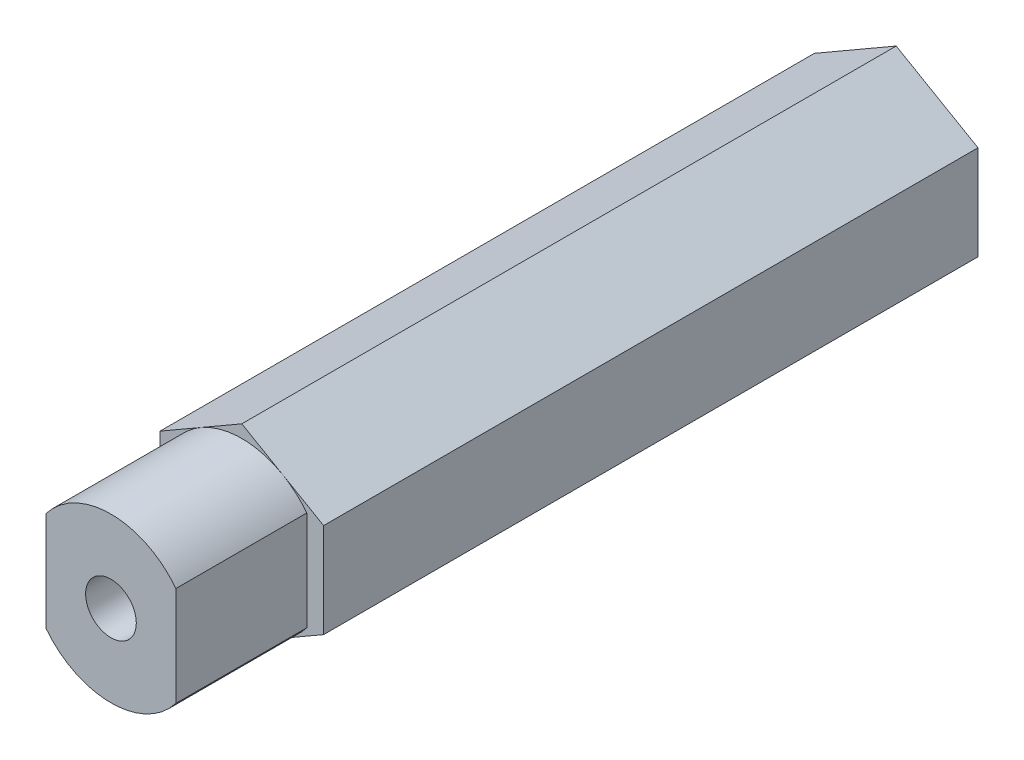
SolidWorks part; units mm, degrees
ref_plane "Front Plane" through (0, 0, 0) normal (0, 0, 1) x (1, 0, 0)
ref_plane "Top Plane" through (0, 0, 0) normal (0, 1, 0) x (1, 0, 0)
ref_plane "Right Plane" through (0, 0, 0) normal (1, 0, 0) x (0, 0, -1)
sketch "Sketch1" plane through (0, 0, 0) normal (0, 0, 1) x (1, 0, 0)
  line L0 (-5, 0) -> (5, 0) construction
  line L9 (0, 5.7735) -> (-5, 2.8868) construction
  line L10 (-5, 2.8868) -> (-5, -2.8868) construction
  line L11 (-5, -2.8868) -> (0, -5.7735) construction
  line L12 (0, -5.7735) -> (5, -2.8868) construction
  line L13 (5, -2.8868) -> (5, 2.8868) construction
  line L14 (5, 2.8868) -> (0, 5.7735) construction
  circle A3 centre (0, 0) radius 5 construction
  point P4 (0, 0)
  dimension "Width" = 10
sketch "Sketch2" plane through (0, 0, 0) normal (1, 0, 0) x (0, 0, -1)
  line L0 (152.4003, 5.7735) -> (-152.4003, 5.7735) construction
  point P3 (-140.9003, 5.7735)
  point P4 (0, 5.7735)
  point P5 (140.9003, 5.7735)
  dimension "Length" = 304.8006
  dimension "D1" = 11.5
  dimension "D2" = 11.5
sketch "Sketch3" plane through (0, 0, 0) normal (0, 0, 1) x (1, 0, 0)
  line L1 (0, 5.7735) -> (5, 2.8868)
  line L2 (5, 2.8868) -> (5, -2.8868)
  line L3 (5, -2.8868) -> (0, -5.7735)
  line L4 (0, -5.7735) -> (-5, -2.8868)
  line L5 (-5, -2.8868) -> (-5, 2.8868)
  line L6 (-5, 2.8868) -> (0, 5.7735)
extrude "Boss-Extrude1" add sketch "Sketch3" along normal mid plane 48
sketch "Sketch4" plane through (0, 0, 24) normal (0, 0, 1) x (1, 0, 0)
  line L0 (3.97, -3.0396) -> (3.97, 3.0396)
  line L1 (-3.97, -3.0396) -> (-3.97, 3.0396)
  line L8 (0, 5.7735) -> (-5, 2.8868)
  line L9 (-5, 2.8868) -> (-5, -2.8868)
  line L10 (-5, -2.8868) -> (0, -5.7735)
  line L11 (0, -5.7735) -> (5, -2.8868)
  line L12 (5, -2.8868) -> (5, 2.8868)
  line L13 (5, 2.8868) -> (0, 5.7735)
  line L14 (0, 5.7735) -> (-5, 2.8868)
  line L15 (-5, 2.8868) -> (-5, -2.8868)
  line L16 (-5, -2.8868) -> (0, -5.7735)
  line L17 (0, -5.7735) -> (5, -2.8868)
  line L18 (5, -2.8868) -> (5, 2.8868)
  line L19 (5, 2.8868) -> (0, 5.7735)
  circle A0 centre (0, 0) radius 1.55
  circle A1 centre (0, 0) radius 5 construction
  arc A2 (-3.97, 3.0396) -> (3.97, 3.0396) centre (0, 0) cw
  arc A3 (-3.97, -3.0396) -> (3.97, -3.0396) centre (0, 0) ccw
  point P9 (0, 0)
  point P10 (0, 0)
  point P11 (0, 0)
  line M3 (0, 5.7735) -> (-5, 2.8868)
  line M4 (-5, 2.8868) -> (-5, -2.8868)
  line M5 (-5, -2.8868) -> (0, -5.7735)
  line M6 (0, -5.7735) -> (5, -2.8868)
  line M7 (5, -2.8868) -> (5, 2.8868)
  line M8 (5, 2.8868) -> (0, 5.7735)
  dimension "D1" = 10
  dimension "D2" = 3.1
  dimension "D3" = 7.94
  dimension "D4" = 0
extrude "Cut-Extrude1" cut sketch "Sketch4" against normal blind 8 contours A3 L1 A2 L14 M4 M5 | A2 L19 M3 | A3 L17 A2 L0 M7 M8 | A3 L16 M6 | A0
equation "\"D1@Boss-Extrude1\" = \"Length@Sketch2\""
equation "\"D1@Sketch2\" = \"Width@Sketch1\" * 1.15"
equation "\"D2@Sketch2\"=\"D1@Sketch2\""
